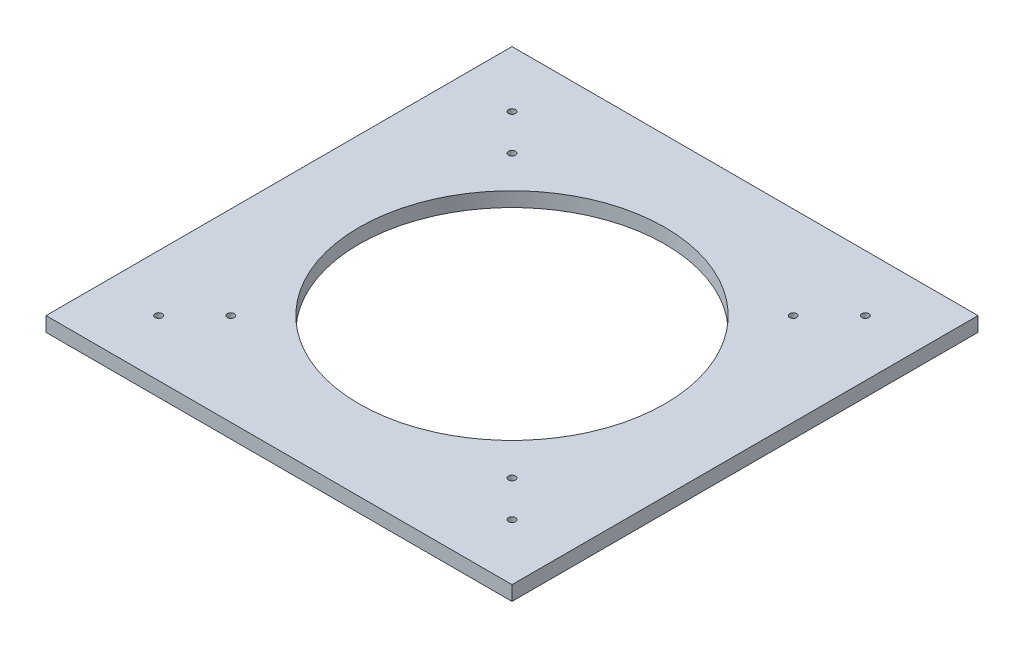
SolidWorks part; units mm, degrees
ref_plane "Front Plane" through (0, 0, 0) normal (0, 0, 1) x (1, 0, 0)
ref_plane "Top Plane" through (0, 0, 0) normal (0, 1, 0) x (1, 0, 0)
ref_plane "Right Plane" through (0, 0, 0) normal (1, 0, 0) x (0, 0, -1)
sketch "Sketch1" plane through (0, 0, 0) normal (0, 1, 0) x (1, 0, 0)
  line L0 (0, 80) -> (0, -80) construction
  line L1 (-80, -80) -> (80, -80)
  line L2 (-80, -80) -> (-80, 80)
  line L3 (-80, 80) -> (80, 80)
  line L4 (80, -80) -> (80, 80)
  line L5 (-80, -80) -> (80, 80) construction
  line L6 (-80, 80) -> (80, -80) construction
  line L7 (-80, 0) -> (80, 0) construction
  circle A0 centre (-60.6642, 60.6642) radius 1.2
  circle A1 centre (-48.2796, 48.2796) radius 1.2
  circle A2 centre (48.2796, 48.2796) radius 1.2
  circle A3 centre (60.6642, 60.6642) radius 1.2
  circle A4 centre (60.6642, -60.6642) radius 1.2
  circle A5 centre (48.2796, -48.2796) radius 1.2
  circle A6 centre (-48.2796, -48.2796) radius 1.2
  circle A7 centre (-60.6642, -60.6642) radius 1.2
  circle A8 centre (0, 0) radius 52.5
  point P0 (0, 0)
  dimension "D2" = 2.4
  dimension "D3" = 2.4
  dimension "D4" = 105
  dimension "D1" = 160
extrude "Boss-Extrude1" add sketch "Sketch1" along normal blind 5
